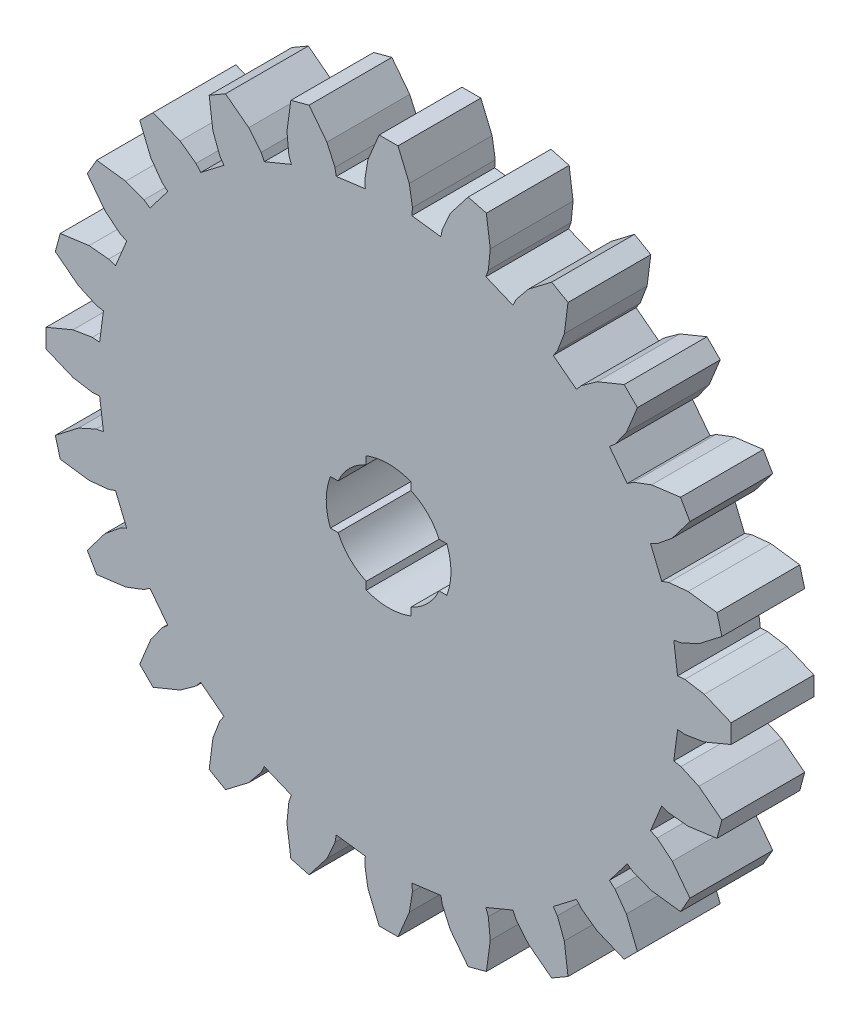
SolidWorks part; units mm, degrees
ref_plane "Front Plane" through (0, 0, 0) normal (0, 0, 1) x (1, 0, 0)
ref_plane "Top Plane" through (0, 0, 0) normal (0, 1, 0) x (1, 0, 0)
ref_plane "Right Plane" through (0, 0, 0) normal (1, 0, 0) x (0, 0, -1)
sketch "Model" plane through (0, 0, 0) normal (0, 0, 1) x (1, 0, 0)
  line L0 (70.7396, 171.3611) -> (71.0026, 171.3823)
  line L1 (71.0026, 171.3823) -> (71.7039, 171.2674)
  line L2 (71.7039, 171.2674) -> (72.6787, 170.8596)
  line L3 (72.6787, 170.8596) -> (72.6787, 170.1764)
  line L4 (72.6787, 170.1764) -> (71.7039, 169.7685)
  line L5 (71.7039, 169.7685) -> (71.0026, 169.6536)
  line L6 (71.0026, 169.6536) -> (70.7396, 169.6748)
  line L7 (70.7396, 169.6748) -> (70.6011, 168.6225)
  line L8 (70.6011, 168.6225) -> (70.8606, 168.5748)
  line L9 (70.8606, 168.5748) -> (71.5082, 168.2824)
  line L10 (71.5082, 168.2824) -> (72.3442, 167.6361)
  line L11 (72.3442, 167.6361) -> (72.1674, 166.9762)
  line L12 (72.1674, 166.9762) -> (71.1203, 166.8345)
  line L13 (71.1203, 166.8345) -> (70.4132, 166.9051)
  line L14 (70.4132, 166.9051) -> (70.1646, 166.9936)
  line L15 (70.1646, 166.9936) -> (69.7584, 166.013)
  line L16 (69.7584, 166.013) -> (69.9968, 165.8998)
  line L17 (69.9968, 165.8998) -> (70.5467, 165.4497)
  line L18 (70.5467, 165.4497) -> (71.1869, 164.6091)
  line L19 (71.1869, 164.6091) -> (70.8453, 164.0174)
  line L20 (70.8453, 164.0174) -> (69.7972, 164.1516)
  line L21 (69.7972, 164.1516) -> (69.1325, 164.4028)
  line L22 (69.1325, 164.4028) -> (68.9153, 164.5526)
  line L23 (68.9153, 164.5526) -> (68.2691, 163.7105)
  line L24 (68.2691, 163.7105) -> (68.4701, 163.5395)
  line L25 (68.4701, 163.5395) -> (68.8847, 162.9624)
  line L26 (68.8847, 162.9624) -> (69.2856, 161.9847)
  line L27 (69.2856, 161.9847) -> (68.8025, 161.5017)
  line L28 (68.8025, 161.5017) -> (67.8248, 161.9025)
  line L29 (67.8248, 161.9025) -> (67.2477, 162.3172)
  line L30 (67.2477, 162.3172) -> (67.0767, 162.5181)
  line L31 (67.0767, 162.5181) -> (66.2346, 161.872)
  line L32 (66.2346, 161.872) -> (66.3845, 161.6548)
  line L33 (66.3845, 161.6548) -> (66.6356, 160.99)
  line L34 (66.6356, 160.99) -> (66.7698, 159.9419)
  line L35 (66.7698, 159.9419) -> (66.1781, 159.6003)
  line L36 (66.1781, 159.6003) -> (65.3375, 160.2406)
  line L37 (65.3375, 160.2406) -> (64.8874, 160.7904)
  line L38 (64.8874, 160.7904) -> (64.7743, 161.0288)
  line L39 (64.7743, 161.0288) -> (63.7936, 160.6226)
  line L40 (63.7936, 160.6226) -> (63.8821, 160.3741)
  line L41 (63.8821, 160.3741) -> (63.9527, 159.6669)
  line L42 (63.9527, 159.6669) -> (63.811, 158.6198)
  line L43 (63.811, 158.6198) -> (63.1511, 158.443)
  line L44 (63.1511, 158.443) -> (62.5048, 159.279)
  line L45 (62.5048, 159.279) -> (62.2124, 159.9266)
  line L46 (62.2124, 159.9266) -> (62.1648, 160.1862)
  line L47 (62.1648, 160.1862) -> (61.1124, 160.0476)
  line L48 (61.1124, 160.0476) -> (61.1336, 159.7846)
  line L49 (61.1336, 159.7846) -> (61.0187, 159.0833)
  line L50 (61.0187, 159.0833) -> (60.6109, 158.1086)
  line L51 (60.6109, 158.1086) -> (59.9277, 158.1086)
  line L52 (59.9277, 158.1086) -> (59.5198, 159.0833)
  line L53 (59.5198, 159.0833) -> (59.4049, 159.7846)
  line L54 (59.4049, 159.7846) -> (59.4261, 160.0476)
  line L55 (59.4261, 160.0476) -> (58.3738, 160.1862)
  line L56 (58.3738, 160.1862) -> (58.3262, 159.9266)
  line L57 (58.3262, 159.9266) -> (58.0337, 159.279)
  line L58 (58.0337, 159.279) -> (57.3875, 158.443)
  line L59 (57.3875, 158.443) -> (56.7275, 158.6198)
  line L60 (56.7275, 158.6198) -> (56.5859, 159.6669)
  line L61 (56.5859, 159.6669) -> (56.6564, 160.3741)
  line L62 (56.6564, 160.3741) -> (56.7449, 160.6226)
  line L63 (56.7449, 160.6226) -> (55.7643, 161.0288)
  line L64 (55.7643, 161.0288) -> (55.6511, 160.7904)
  line L65 (55.6511, 160.7904) -> (55.201, 160.2406)
  line L66 (55.201, 160.2406) -> (54.3604, 159.6003)
  line L67 (54.3604, 159.6003) -> (53.7687, 159.9419)
  line L68 (53.7687, 159.9419) -> (53.9029, 160.99)
  line L69 (53.9029, 160.99) -> (54.1541, 161.6548)
  line L70 (54.1541, 161.6548) -> (54.3039, 161.872)
  line L71 (54.3039, 161.872) -> (53.4618, 162.5181)
  line L72 (53.4618, 162.5181) -> (53.2908, 162.3172)
  line L73 (53.2908, 162.3172) -> (52.7137, 161.9025)
  line L74 (52.7137, 161.9025) -> (51.7361, 161.5017)
  line L75 (51.7361, 161.5017) -> (51.253, 161.9847)
  line L76 (51.253, 161.9847) -> (51.6538, 162.9624)
  line L77 (51.6538, 162.9624) -> (52.0685, 163.5395)
  line L78 (52.0685, 163.5395) -> (52.2694, 163.7105)
  line L79 (52.2694, 163.7105) -> (51.6233, 164.5526)
  line L80 (51.6233, 164.5526) -> (51.4061, 164.4028)
  line L81 (51.4061, 164.4028) -> (50.7413, 164.1516)
  line L82 (50.7413, 164.1516) -> (49.6932, 164.0174)
  line L83 (49.6932, 164.0174) -> (49.3516, 164.6091)
  line L84 (49.3516, 164.6091) -> (49.9919, 165.4497)
  line L85 (49.9919, 165.4497) -> (50.5418, 165.8998)
  line L86 (50.5418, 165.8998) -> (50.7801, 166.013)
  line L87 (50.7801, 166.013) -> (50.3739, 166.9936)
  line L88 (50.3739, 166.9936) -> (50.1254, 166.9051)
  line L89 (50.1254, 166.9051) -> (49.4183, 166.8345)
  line L90 (49.4183, 166.8345) -> (48.3711, 166.9762)
  line L91 (48.3711, 166.9762) -> (48.1943, 167.6361)
  line L92 (48.1943, 167.6361) -> (49.0303, 168.2824)
  line L93 (49.0303, 168.2824) -> (49.678, 168.5748)
  line L94 (49.678, 168.5748) -> (49.9375, 168.6225)
  line L95 (49.9375, 168.6225) -> (49.7989, 169.6748)
  line L96 (49.7989, 169.6748) -> (49.5359, 169.6536)
  line L97 (49.5359, 169.6536) -> (48.8347, 169.7685)
  line L98 (48.8347, 169.7685) -> (47.8599, 170.1764)
  line L99 (47.8599, 170.1764) -> (47.8599, 170.8596)
  line L100 (47.8599, 170.8596) -> (48.8347, 171.2674)
  line L101 (48.8347, 171.2674) -> (49.5359, 171.3823)
  line L102 (49.5359, 171.3823) -> (49.7989, 171.3611)
  line L103 (49.7989, 171.3611) -> (49.9375, 172.4135)
  line L104 (49.9375, 172.4135) -> (49.678, 172.4611)
  line L105 (49.678, 172.4611) -> (49.0303, 172.7535)
  line L106 (49.0303, 172.7535) -> (48.1943, 173.3998)
  line L107 (48.1943, 173.3998) -> (48.3711, 174.0597)
  line L108 (48.3711, 174.0597) -> (49.4183, 174.2014)
  line L109 (49.4183, 174.2014) -> (50.1254, 174.1308)
  line L110 (50.1254, 174.1308) -> (50.3739, 174.0423)
  line L111 (50.3739, 174.0423) -> (50.7801, 175.0229)
  line L112 (50.7801, 175.0229) -> (50.5418, 175.1361)
  line L113 (50.5418, 175.1361) -> (49.9919, 175.5862)
  line L114 (49.9919, 175.5862) -> (49.3516, 176.4268)
  line L115 (49.3516, 176.4268) -> (49.6932, 177.0185)
  line L116 (49.6932, 177.0185) -> (50.7413, 176.8843)
  line L117 (50.7413, 176.8843) -> (51.4061, 176.6332)
  line L118 (51.4061, 176.6332) -> (51.6233, 176.4833)
  line L119 (51.6233, 176.4833) -> (52.2694, 177.3254)
  line L120 (52.2694, 177.3254) -> (52.0685, 177.4964)
  line L121 (52.0685, 177.4964) -> (51.6538, 178.0735)
  line L122 (51.6538, 178.0735) -> (51.253, 179.0512)
  line L123 (51.253, 179.0512) -> (51.7361, 179.5343)
  line L124 (51.7361, 179.5343) -> (52.7137, 179.1334)
  line L125 (52.7137, 179.1334) -> (53.2908, 178.7188)
  line L126 (53.2908, 178.7188) -> (53.4618, 178.5178)
  line L127 (53.4618, 178.5178) -> (54.3039, 179.164)
  line L128 (54.3039, 179.164) -> (54.1541, 179.3811)
  line L129 (54.1541, 179.3811) -> (53.9029, 180.0459)
  line L130 (53.9029, 180.0459) -> (53.7687, 181.094)
  line L131 (53.7687, 181.094) -> (54.3604, 181.4356)
  line L132 (54.3604, 181.4356) -> (55.201, 180.7954)
  line L133 (55.201, 180.7954) -> (55.6511, 180.2455)
  line L134 (55.6511, 180.2455) -> (55.7643, 180.0071)
  line L135 (55.7643, 180.0071) -> (56.7449, 180.4133)
  line L136 (56.7449, 180.4133) -> (56.6564, 180.6619)
  line L137 (56.6564, 180.6619) -> (56.5859, 181.369)
  line L138 (56.5859, 181.369) -> (56.7275, 182.4161)
  line L139 (56.7275, 182.4161) -> (57.3875, 182.5929)
  line L140 (57.3875, 182.5929) -> (58.0337, 181.7569)
  line L141 (58.0337, 181.7569) -> (58.3262, 181.1093)
  line L142 (58.3262, 181.1093) -> (58.3738, 180.8498)
  line L143 (58.3738, 180.8498) -> (59.4261, 180.9883)
  line L144 (59.4261, 180.9883) -> (59.4049, 181.2513)
  line L145 (59.4049, 181.2513) -> (59.5198, 181.9526)
  line L146 (59.5198, 181.9526) -> (59.9277, 182.9273)
  line L147 (59.9277, 182.9273) -> (60.6109, 182.9273)
  line L148 (60.6109, 182.9273) -> (61.0187, 181.9526)
  line L149 (61.0187, 181.9526) -> (61.1336, 181.2513)
  line L150 (61.1336, 181.2513) -> (61.1124, 180.9883)
  line L151 (61.1124, 180.9883) -> (62.1648, 180.8498)
  line L152 (62.1648, 180.8498) -> (62.2124, 181.1093)
  line L153 (62.2124, 181.1093) -> (62.5048, 181.7569)
  line L154 (62.5048, 181.7569) -> (63.1511, 182.5929)
  line L155 (63.1511, 182.5929) -> (63.811, 182.4161)
  line L156 (63.811, 182.4161) -> (63.9527, 181.369)
  line L157 (63.9527, 181.369) -> (63.8821, 180.6619)
  line L158 (63.8821, 180.6619) -> (63.7936, 180.4133)
  line L159 (63.7936, 180.4133) -> (64.7743, 180.0071)
  line L160 (64.7743, 180.0071) -> (64.8874, 180.2455)
  line L161 (64.8874, 180.2455) -> (65.3375, 180.7954)
  line L162 (65.3375, 180.7954) -> (66.1781, 181.4356)
  line L163 (66.1781, 181.4356) -> (66.7698, 181.094)
  line L164 (66.7698, 181.094) -> (66.6356, 180.0459)
  line L165 (66.6356, 180.0459) -> (66.3845, 179.3811)
  line L166 (66.3845, 179.3811) -> (66.2346, 179.164)
  line L167 (66.2346, 179.164) -> (67.0767, 178.5178)
  line L168 (67.0767, 178.5178) -> (67.2477, 178.7188)
  line L169 (67.2477, 178.7188) -> (67.8248, 179.1334)
  line L170 (67.8248, 179.1334) -> (68.8025, 179.5343)
  line L171 (68.8025, 179.5343) -> (69.2856, 179.0512)
  line L172 (69.2856, 179.0512) -> (68.8847, 178.0735)
  line L173 (68.8847, 178.0735) -> (68.4701, 177.4964)
  line L174 (68.4701, 177.4964) -> (68.2691, 177.3254)
  line L175 (68.2691, 177.3254) -> (68.9153, 176.4833)
  line L176 (68.9153, 176.4833) -> (69.1325, 176.6332)
  line L177 (69.1325, 176.6332) -> (69.7972, 176.8843)
  line L178 (69.7972, 176.8843) -> (70.8453, 177.0185)
  line L179 (70.8453, 177.0185) -> (71.1869, 176.4268)
  line L180 (71.1869, 176.4268) -> (70.5467, 175.5862)
  line L181 (70.5467, 175.5862) -> (69.9968, 175.1361)
  line L182 (69.9968, 175.1361) -> (69.7584, 175.0229)
  line L183 (69.7584, 175.0229) -> (70.1646, 174.0423)
  line L184 (70.1646, 174.0423) -> (70.4132, 174.1308)
  line L185 (70.4132, 174.1308) -> (71.1203, 174.2014)
  line L186 (71.1203, 174.2014) -> (72.1674, 174.0597)
  line L187 (72.1674, 174.0597) -> (72.3442, 173.3998)
  line L188 (72.3442, 173.3998) -> (71.5082, 172.7535)
  line L189 (71.5082, 172.7535) -> (70.8606, 172.4611)
  line L190 (70.8606, 172.4611) -> (70.6011, 172.4135)
  line L191 (70.6011, 172.4135) -> (70.7396, 171.3611)
extrude "Boss-Extrude1" add sketch "Model" along normal blind 3
sketch "Sketch2" plane through (0, 0, 3) normal (0, 0, 1) x (1, 0, 0)
  line L0 (49.8682, 171.8873) -> (70.6703, 169.1486) construction
  line L1 (49.9375, 172.4135) -> (49.7989, 171.3611) construction
  line L2 (70.6011, 168.6225) -> (70.7396, 169.6748) construction
  circle A0 centre (60.2693, 170.518) radius 2
  dimension "D1" = 4
extrude "Cut-Extrude1" cut sketch "Sketch2" against normal blind 3
sketch "Sketch3" plane through (0, 0, 3) normal (0, 0, 1) x (1, 0, 0)
  line L0 (58.1594, 171.328) -> (59.4593, 171.328)
  line L1 (62.3791, 169.708) -> (58.1594, 169.708) construction
  line L2 (62.3791, 169.708) -> (62.3791, 171.328) construction
  line L3 (62.3791, 171.328) -> (58.1594, 171.328) construction
  line L4 (58.1594, 169.708) -> (58.1594, 171.328) construction
  line L5 (62.3791, 169.708) -> (58.1594, 171.328) construction
  line L6 (62.3791, 171.328) -> (58.1594, 169.708) construction
  line L7 (59.4593, 168.4081) -> (61.0793, 168.4081) construction
  line L8 (59.4593, 168.4081) -> (59.4593, 172.6278) construction
  line L9 (59.4593, 172.6278) -> (61.0793, 172.6278) construction
  line L10 (61.0793, 168.4081) -> (61.0793, 172.6278) construction
  line L11 (59.4593, 168.4081) -> (61.0793, 172.6278) construction
  line L12 (59.4593, 172.6278) -> (61.0793, 168.4081) construction
  line L13 (59.4593, 171.328) -> (59.4593, 172.6278)
  line L14 (61.0793, 172.6278) -> (61.0793, 171.328)
  line L15 (61.0793, 171.328) -> (62.3791, 171.328)
  line L16 (62.3791, 169.708) -> (61.0793, 169.708)
  line L17 (61.0793, 169.708) -> (61.0793, 168.4081)
  line L18 (59.4593, 168.4081) -> (59.4593, 169.708)
  line L19 (59.4593, 169.708) -> (58.1594, 169.708)
  line L20 (49.8682, 171.8873) -> (70.6703, 169.1486) construction
  line L21 (49.9375, 172.4135) -> (49.7989, 171.3611) construction
  line L22 (70.6011, 168.6225) -> (70.7396, 169.6748) construction
  circle A0 centre (60.2693, 170.518) radius 2.26 construction
  spline S0 degree 2 poles (58.1594, 169.708) (57.8591, 170.518) (58.1594, 171.328) knots 0 0 0 1 1 1
  spline S1 degree 2 poles (59.4593, 172.6278) (60.2693, 172.9281) (61.0793, 172.6278) knots 0 0 0 1 1 1
  spline S2 degree 2 poles (62.3791, 171.328) (62.6794, 170.518) (62.3791, 169.708) knots 0 0 0 1 1 1
  spline S3 degree 2 poles (61.0793, 168.4081) (60.2693, 168.1078) (59.4593, 168.4081) knots 0 0 0 1 1 1
extrude "Cut-Extrude2" cut sketch "Sketch3" against normal blind 3
